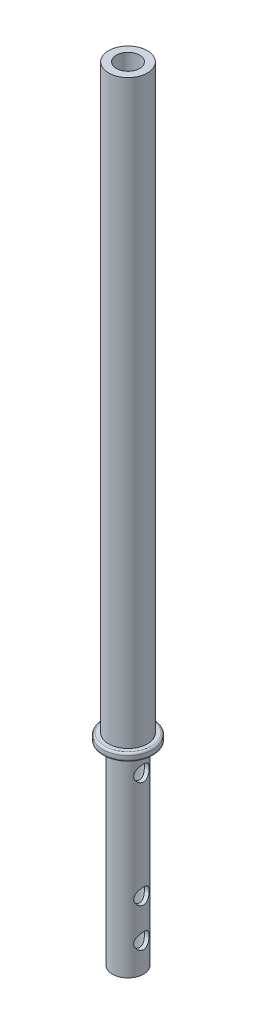
SolidWorks part; units mm, degrees
ref_plane "Front Plane" through (0, 0, 0) normal (0, 0, 1) x (1, 0, 0)
ref_plane "Top Plane" through (0, 0, 0) normal (0, 1, 0) x (1, 0, 0)
ref_plane "Right Plane" through (0, 0, 0) normal (1, 0, 0) x (0, 0, -1)
sketch "Sketch1" plane through (0, 0, 0) normal (1, 0, 0) x (0, 0, -1)
  line L0 (0, 0) -> (0, 300)
  line L1 (0, 300) -> (10, 300)
  line L2 (10, 300) -> (10, 0)
  line L3 (10, 0) -> (13, 0)
  line L4 (13, 0) -> (13, -4)
  line L5 (13, -4) -> (8, -4)
  line L6 (8, -4) -> (8, -104)
  line L7 (8, -104) -> (0, -104)
  line L8 (0, -104) -> (0, 0)
  dimension "D1" = 300
  dimension "D2" = 100
  dimension "D3" = 4
  dimension "D4" = 10
  dimension "D5" = 8
  dimension "D6" = 3
revolve "Revolve1" add sketch "Sketch1" angle 360 about L0
sketch "Sketch2" plane through (0, 300, 0) normal (0, 1, 0) x (1, 0, 0)
  circle A0 centre (0, 0) radius 6
  dimension "D1" = 12
extrude "Cut-Extrude1" cut sketch "Sketch2" against normal through all
sketch "Sketch3" plane through (0, 0, 0) normal (1, 0, 0) x (0, 0, -1)
  line L0 (-8, -104) -> (8, -104) construction
  circle A0 centre (0, -14) radius 4
  circle A1 centre (0, -69) radius 4
  circle A2 centre (0, -89) radius 4
  dimension "D1" = 8
  dimension "D2" = 15
  dimension "D3" = 20
  dimension "D4" = 90
extrude "Cut-Extrude3" cut sketch "Sketch3" against normal through all both and the other way through all
fillet "Fillet1" radius 1 2 edges at (0, -4, -13) (0, 0, -13)
